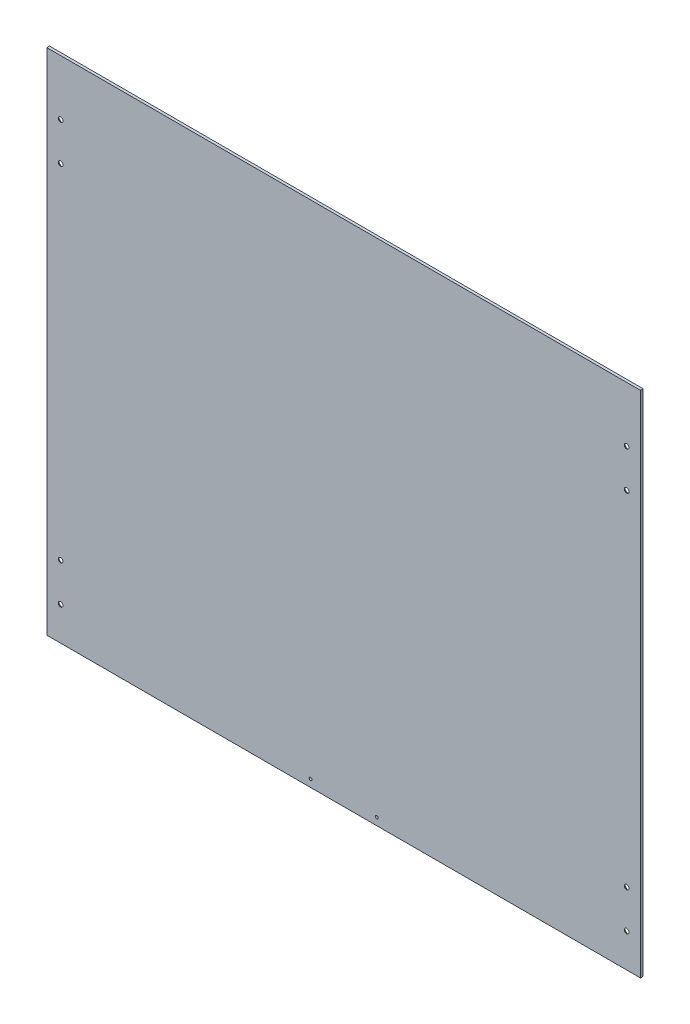
SolidWorks part; units mm, degrees
material "6061-T6 ALUMINUM"
ref_plane "Front/Back" through (0, 0, 0) normal (0, 0, 1) x (1, 0, 0)
ref_plane "Top/Bottom" through (0, 0, 0) normal (0, 1, 0) x (1, 0, 0)
ref_plane "Right/Left" through (0, 0, 0) normal (1, 0, 0) x (0, 0, -1)
sketch "Sketch1" plane through (0, 0, 0) normal (0, 0, 1) x (1, 0, 0)
  line L1 (-350, 300) -> (350, 300)
  line L2 (-350, 300) -> (-350, -300)
  line L3 (-350, -300) -> (350, -300)
  line L4 (350, 300) -> (350, -300)
  line L5 (0, 0) -> (350, 0) construction
  line L6 (0, 0) -> (0, 300) construction
  dimension "D1" = 700
  dimension "D2" = 600
extrude "Extrude1" add sketch "Sketch1" along normal mid plane 3.175
hole_wizard "CSK for M5 SFHCS2" positions "Sketch5" profile "Sketch4" countersink size "M5" standard "_*ATS Preferred Ansi METRIC" end condition through all
sketch "Sketch5" plane through (0, 0, -1.5875) normal (0, 0, -1) x (-1, 0, 0)
  point P1 (-333.65, 234.7)
  point P4 (-333.65, 189.7)
  point P7 (-333.65, -215.3)
  point P10 (-333.65, -260.3)
  point P13 (333.65, -260.3)
  point P16 (333.65, -215.3)
  point P19 (333.65, 189.7)
  point P22 (333.65, 234.7)
sketch "Sketch4" plane through (333.65, 234.7, -1.5875) normal (1, 0, 0) x (0, 1, 0)
  line L0 (0, 0) -> (0, 3.175)
  line L1 (0, 3.175) -> (2.75, 3.175)
  line L2 (2.75, 3.175) -> (2.75, 3)
  line L3 (2.75, 3) -> (5.75, 0)
  line L5 (5.75, 0) -> (0, 0)
  line L6 (-2.75, 3) -> (-5.75, 0) construction
  line L11 (0, -6.35) -> (0, 107.95) construction
  dimension "Thru Hole Dia." = 5.5
  dimension "Thru Hole Depth" = 3.175
  dimension "Near C'Sink Dia." = 11.5
  dimension "Near C'Sink Angle" = 90
hole_wizard "M4x0.7 Tapped Hole1" positions "Sketch7" profile "Sketch6" tap size "M4x0.7" standard "_*ATS Preferred Ansi METRIC" end condition through all
sketch "Sketch7" plane through (0, 0, 1.5875) normal (0, 0, 1) x (1, 0, 0)
  line L0 (39, -289.5) -> (39, -293) construction
  line L3 (-39, -289.5) -> (-39, -293) construction
  point P0 (-39, -291.25)
  point P1 (39, -291.25)
sketch "Sketch6" plane through (-39, -291.25, 1.5875) normal (1, 0, 0) x (0, -1, 0)
  line L0 (0, 0) -> (0, 3.175)
  line L1 (0, 3.175) -> (1.65, 3.175)
  line L2 (1.65, 3.175) -> (1.65, 0)
  line L5 (1.65, 0) -> (0, 0)
  line L11 (0, -6.35) -> (0, 107.95) construction
  dimension "Thru Tap Drill Dia." = 3.3
  dimension "Thru Tap Drill Depth" = 3.175
cosmetic thread "Hole Thread1" parameters "D2"=4
cosmetic thread "Hole Thread2" parameters "D2"=4
